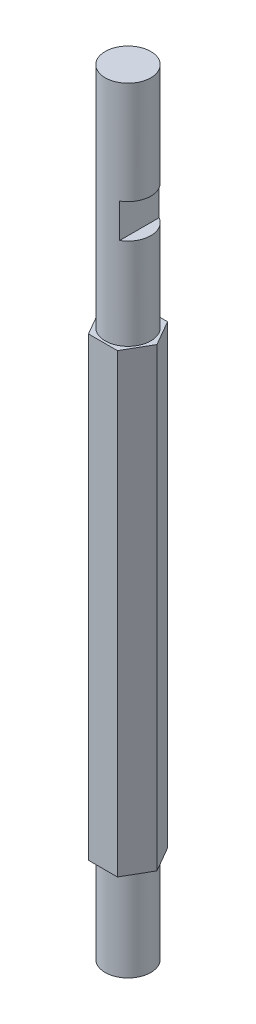
SolidWorks part; units mm, degrees
ref_plane "Ön Düzlem" through (0, 0, 0) normal (0, 0, 1) x (1, 0, 0)
ref_plane "Üst Düzlem" through (0, 0, 0) normal (0, 1, 0) x (1, 0, 0)
ref_plane "Sağ Düzlem" through (0, 0, 0) normal (1, 0, 0) x (0, 0, -1)
sketch "Sketch1" plane through (0, 0, 0) normal (0, 1, 0) x (1, 0, 0)
  line L1 (12.7017, 0) -> (6.3509, 11)
  line L2 (6.3509, 11) -> (-6.3509, 11)
  line L3 (-6.3509, 11) -> (-12.7017, 0)
  line L4 (-12.7017, 0) -> (-6.3509, -11)
  line L5 (-6.3509, -11) -> (6.3509, -11)
  line L6 (6.3509, -11) -> (12.7017, 0)
  circle A0 centre (0, 0) radius 11 construction
  dimension "D1" = 22
extrude "Boss-Extrude1" add sketch "Sketch1" along normal blind 200
sketch "Sketch4" plane through (0, 0, 0) normal (0, -1, 0) x (1, 0, 0)
  circle A0 centre (0, 0) radius 10
  dimension "D1" = 20
extrude "Boss-Extrude4" add sketch "Sketch4" along normal blind 40
sketch "Sketch5" plane through (0, 200, 0) normal (0, 1, 0) x (1, 0, 0)
  circle A0 centre (0, 0) radius 10
  dimension "D1" = 20
extrude "Boss-Extrude5" add sketch "Sketch5" along normal blind 100
sketch "Sketch6" plane through (0, 0, 0) normal (0, 0, 1) x (1, 0, 0)
  line L0 (10, 240) -> (5, 240)
  line L1 (10, 200) -> (10, 300) construction
  line L2 (5, 240) -> (5, 255)
  line L3 (5, 255) -> (10, 255)
  line L4 (10, 255) -> (10, 240)
  line L5 (10, 200) -> (-10, 200) construction
  dimension "D1" = 15
  dimension "D2" = 40
  dimension "D3" = 5
extrude "Cut-Extrude1" cut sketch "Sketch6" against normal up to next and the other way up to next
